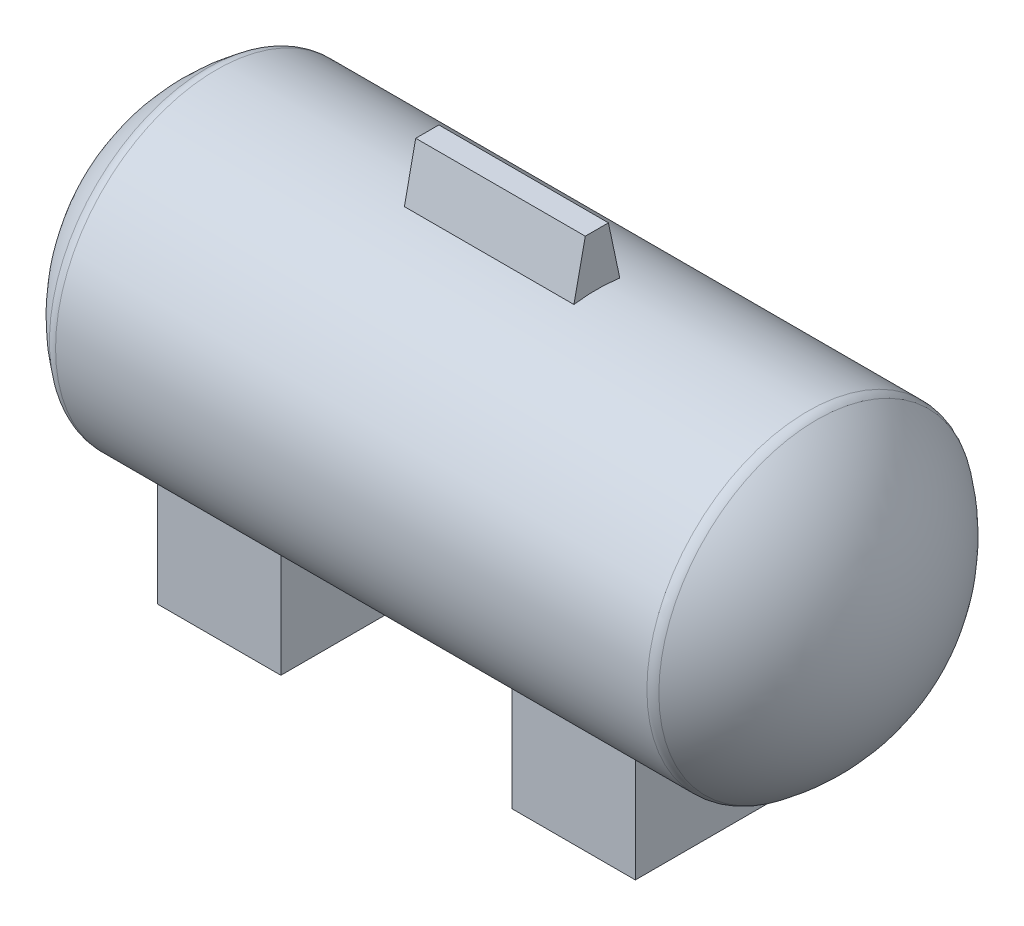
SolidWorks part; units mm, degrees
material "ABS"
ref_plane "正面" through (0, 0, 0) normal (0, 0, 1) x (1, 0, 0)
ref_plane "平面" through (0, 0, 0) normal (0, 1, 0) x (1, 0, 0)
ref_plane "右側面" through (0, 0, 0) normal (1, 0, 0) x (0, 0, -1)
sketch "ｽｹｯﾁ1" plane through (0, 0, 0) normal (0, 0, 1) x (1, 0, 0)
  line L0 (-19.5, 0) -> (19.5, 0) construction
  line L1 (-19.5, 10.4355) -> (19.5, 10.4355)
  line L2 (-25, 0) -> (25, 0)
  arc A0 (-19.5, 10.4355) -> (-25, 0) centre (-12.35, 0) ccw
  arc A1 (19.5, 10.4355) -> (25, 0) centre (12.35, 0) cw
  dimension "D2" = 12.65
  dimension "D3" = 12.65
  dimension "D1" = 39
  dimension "D4" = 39
  dimension "D5" = 5.5
  dimension "D6" = 5.5
revolve "回転2" add sketch "ｽｹｯﾁ1" angle 360 about L0
sketch "ｽｹｯﾁ3" plane through (0, 0, 0) normal (0, 1, 0) x (1, 0, 0)
  line L0 (-25, 0) -> (25, 0) construction
  line L1 (-19.5, -10.4355) -> (-19.5, 10.4355) construction
  line L2 (-7.5, -7.5) -> (-15.5, -7.5)
  line L3 (-7.5, -7.5) -> (-7.5, 7.5)
  line L4 (-7.5, 7.5) -> (-15.5, 7.5)
  line L5 (-15.5, -7.5) -> (-15.5, 7.5)
  line L6 (-7.5, -7.5) -> (-15.5, 7.5) construction
  line L7 (-7.5, 7.5) -> (-15.5, -7.5) construction
  line L8 (15.5, -7.5) -> (7.5, -7.5)
  line L9 (15.5, -7.5) -> (15.5, 7.5)
  line L10 (15.5, 7.5) -> (7.5, 7.5)
  line L11 (7.5, -7.5) -> (7.5, 7.5)
  line L12 (15.5, -7.5) -> (7.5, 7.5) construction
  line L13 (15.5, 7.5) -> (7.5, -7.5) construction
  line L14 (19.5, -10.4355) -> (19.5, 10.4355) construction
  arc A0 (-19.5, 10.4355) -> (-19.5, -10.4355) centre (-12.35, 0) ccw construction
  arc A1 (19.5, -10.4355) -> (19.5, 10.4355) centre (12.35, 0) ccw construction
  point P8 (-11.5, 0)
  point P13 (11.5, 0)
  dimension "D1" = 4
  dimension "D2" = 4
  dimension "D3" = 15
  dimension "D4" = 15
  dimension "D5" = 8
  dimension "D6" = 8
extrude "ﾎﾞｽ - 押し出し1" add sketch "ｽｹｯﾁ3" against normal blind 14
sketch "ｽｹｯﾁ4" plane through (0, -14, 0) normal (0, -1, 0) x (-1, 0, 0)
  line L0 (-11.5, 7.5) -> (-11.5, -7.5) construction
  line L1 (-15.5, 7.5) -> (-7.5, 7.5) construction
  line L2 (-7.5, -7.5) -> (-15.5, -7.5) construction
  line L3 (-11.5, -7.5) -> (11.5, 7.5) construction
  line L4 (7.5, 7.5) -> (15.5, 7.5) construction
  line L5 (11.5, 7.5) -> (11.5, -7.5) construction
  line L6 (15.5, -7.5) -> (7.5, -7.5) construction
  line L7 (11.5, -7.5) -> (-11.5, 7.5) construction
  circle A0 centre (-11.5, 0) radius 1.5
  circle A1 centre (11.5, 0) radius 1.5
  dimension "D1" = 3
  dimension "D2" = 3
extrude "ｶｯﾄ - 押し出し1" cut sketch "ｽｹｯﾁ4" against normal blind 10
fillet "ﾌｨﾚｯﾄ1" radius 1 2 edges at (-19.5, 0, 10.4355) (19.5, 0, 10.4355)
sketch "ｽｹｯﾁ5" plane through (0, 0, 0) normal (1, 0, 0) x (0, 0, -1)
  line L0 (0, 0) -> (0, 11.8528) construction
  line L1 (-1.6, 9.8) -> (1.6, 9.8)
  line L2 (1.6, 9.8) -> (0.75, 13.8)
  line L3 (0.75, 13.8) -> (-0.75, 13.8)
  line L4 (-0.75, 13.8) -> (-1.6, 9.8)
  point P6 (0, 9.8)
  point P10 (0, 13.8)
  dimension "D1" = 9.8
  dimension "D2" = 1.5
  dimension "D3" = 4
  dimension "D4" = 3.2
extrude "ﾎﾞｽ - 押し出し2" add sketch "ｽｹｯﾁ5" along normal mid plane 11
